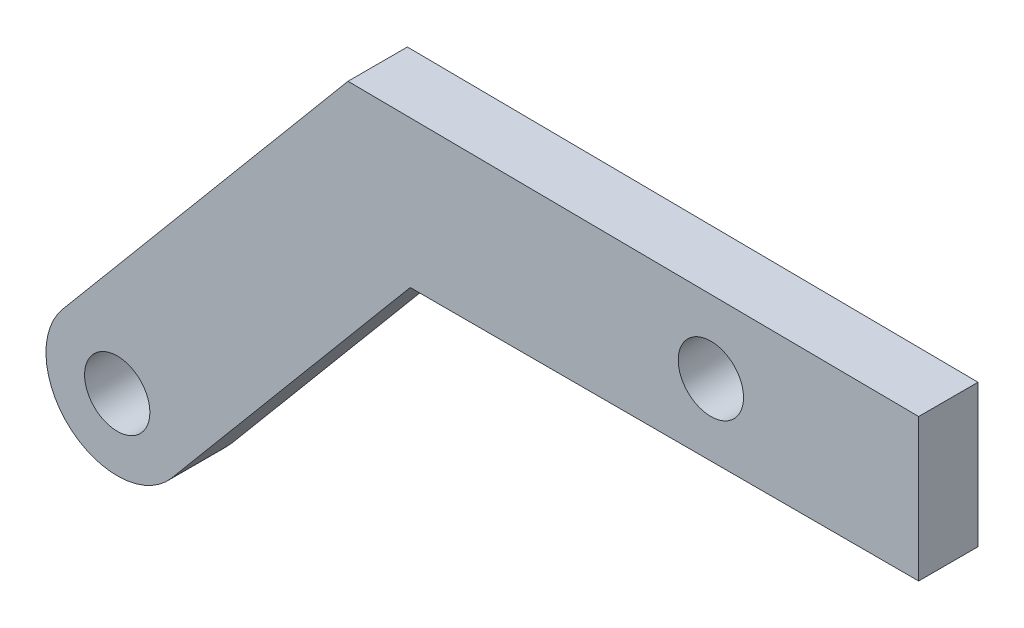
SolidWorks part; units mm, degrees
ref_plane "Front Plane" through (0, 0, 0) normal (0, 0, 1) x (1, 0, 0)
ref_plane "Top Plane" through (0, 0, 0) normal (0, 1, 0) x (1, 0, 0)
ref_plane "Right Plane" through (0, 0, 0) normal (1, 0, 0) x (0, 0, -1)
sketch "Sketch1" plane through (0, 0, 0) normal (0, 0, 1) x (1, 0, 0)
  line L0 (9.1925, -7.7135) -> (39.7116, 28.6578)
  line L1 (0, 0) -> (55.8051, 0) construction
  line L2 (-9.1925, 7.7135) -> (38.8766, 65)
  line L3 (38.8766, 65) -> (135, 64.1529)
  line L4 (135, 64.1529) -> (135, 40.1529)
  line L5 (135, 40.1529) -> (49.3572, 40.1529)
  line L6 (39.7116, 28.6578) -> (49.3572, 40.1529)
  circle A0 centre (0, 0) radius 5.5
  arc A1 (-9.1925, 7.7135) -> (9.1925, -7.7135) centre (0, 0) ccw
  circle A2 centre (100, 52.1529) radius 5.5
  dimension "D1" = 50
  dimension "D3" = 11
  dimension "D4" = 24
  dimension "D6" = 35
  dimension "D2" = 65
  dimension "D5" = 135
extrude "Boss-Extrude1" add sketch "Sketch1" along normal blind 10
